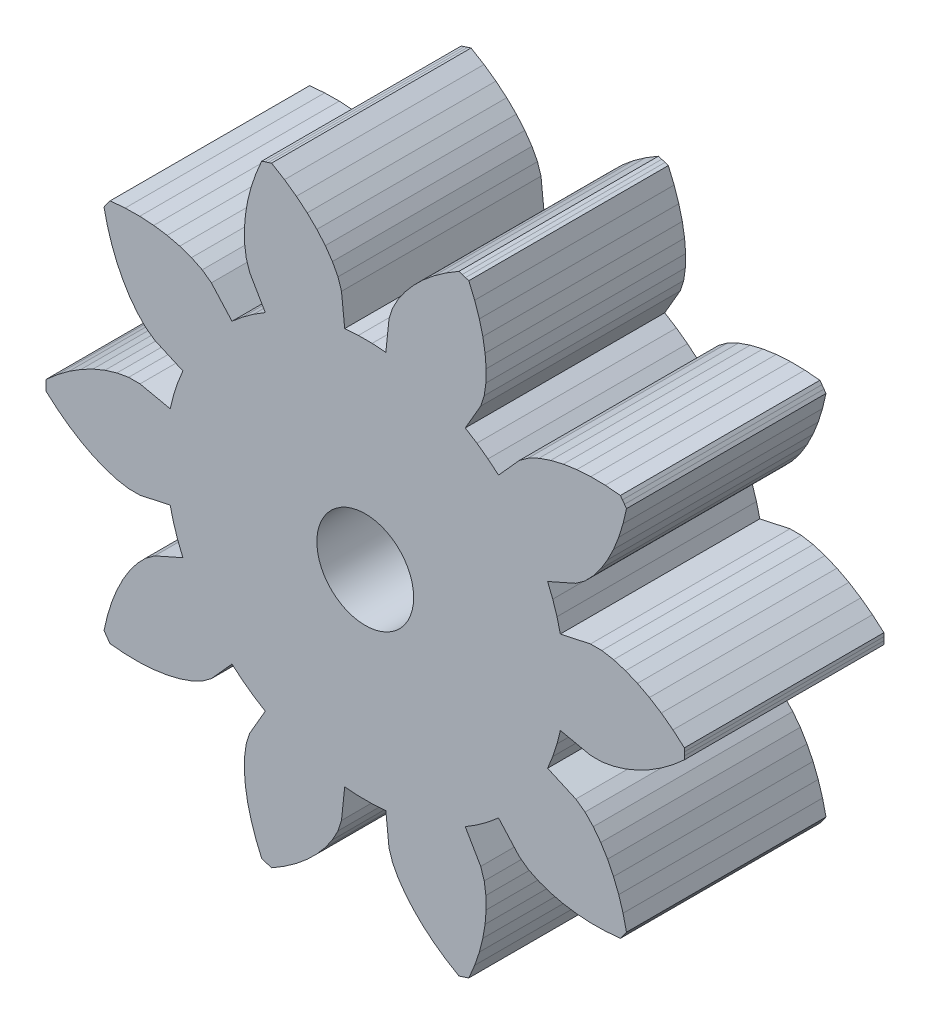
SolidWorks part; units mm, degrees
ref_plane "前视基准面" through (0, 0, 0) normal (0, 0, 1) x (1, 0, 0)
ref_plane "上视基准面" through (0, 0, 0) normal (0, 1, 0) x (1, 0, 0)
ref_plane "右视基准面" through (0, 0, 0) normal (1, 0, 0) x (0, 0, -1)
other "Configuration Table"
sketch "草图1" plane through (0, 0, 0) normal (0, 0, 1) x (1, 0, 0)
  line L0 (14.6679, -3.1391) -> (16.937, -3.6247)
  line L1 (16.937, -3.6247) -> (17.7897, -3.6258)
  line L2 (17.7897, -3.6258) -> (18.6707, -3.47)
  line L3 (18.6707, -3.47) -> (19.5656, -3.1987)
  line L4 (19.5656, -3.1987) -> (20.4663, -2.8243)
  line L5 (20.4663, -2.8243) -> (21.366, -2.3529)
  line L6 (21.366, -2.3529) -> (22.2584, -1.7882)
  line L7 (22.2584, -1.7882) -> (23.1373, -1.133)
  line L8 (23.1373, -1.133) -> (23.9968, -0.3893)
  line L9 (23.9968, -0.3893) -> (23.9996, -0.1298)
  line L10 (23.9996, -0.1298) -> (23.9996, 0.1298)
  line L11 (23.9996, 0.1298) -> (23.9968, 0.3893)
  line L12 (23.9968, 0.3893) -> (23.1373, 1.133)
  line L13 (23.1373, 1.133) -> (22.2584, 1.7882)
  line L14 (22.2584, 1.7882) -> (21.366, 2.3529)
  line L15 (21.366, 2.3529) -> (20.4663, 2.8243)
  line L16 (20.4663, 2.8243) -> (19.5656, 3.1987)
  line L17 (19.5656, 3.1987) -> (18.6707, 3.47)
  line L18 (18.6707, 3.47) -> (17.7897, 3.6258)
  line L19 (17.7897, 3.6258) -> (16.937, 3.6247)
  line L20 (16.937, 3.6247) -> (14.6679, 3.1391)
  line L21 (14.6679, 3.1391) -> (14.417, 4.1412)
  line L22 (14.417, 4.1412) -> (14.0978, 5.1238)
  line L23 (14.0978, 5.1238) -> (13.7117, 6.082)
  line L24 (13.7117, 6.082) -> (15.8329, 7.0229)
  line L25 (15.8329, 7.0229) -> (16.5234, 7.5232)
  line L26 (16.5234, 7.5232) -> (17.1445, 8.167)
  line L27 (17.1445, 8.167) -> (17.709, 8.9125)
  line L28 (17.709, 8.9125) -> (18.2177, 9.7449)
  line L29 (18.2177, 9.7449) -> (18.6685, 10.6551)
  line L30 (18.6685, 10.6551) -> (19.0585, 11.6364)
  line L31 (19.0585, 11.6364) -> (19.3845, 12.6832)
  line L32 (19.3845, 12.6832) -> (19.6427, 13.79)
  line L33 (19.6427, 13.79) -> (19.4924, 14.0016)
  line L34 (19.4924, 14.0016) -> (19.3398, 14.2116)
  line L35 (19.3398, 14.2116) -> (19.185, 14.42)
  line L36 (19.185, 14.42) -> (18.0525, 14.5164)
  line L37 (18.0525, 14.5164) -> (16.9563, 14.5299)
  line L38 (16.9563, 14.5299) -> (15.9025, 14.4622)
  line L39 (15.9025, 14.4622) -> (14.8975, 14.3147)
  line L40 (14.8975, 14.3147) -> (13.9487, 14.0882)
  line L41 (13.9487, 14.0882) -> (13.0653, 13.7816)
  line L42 (13.0653, 13.7816) -> (12.261, 13.3899)
  line L43 (12.261, 13.3899) -> (11.5718, 12.8878)
  line L44 (11.5718, 12.8878) -> (10.0214, 11.1611)
  line L45 (10.0214, 11.1611) -> (9.2294, 11.8244)
  line L46 (9.2294, 11.8244) -> (8.3937, 12.4317)
  line L47 (8.3937, 12.4317) -> (7.5181, 12.9799)
  line L48 (7.5181, 12.9799) -> (8.6811, 14.9879)
  line L49 (8.6811, 14.9879) -> (8.9457, 15.7986)
  line L50 (8.9457, 15.7986) -> (9.0697, 16.6846)
  line L51 (9.0697, 16.6846) -> (9.0883, 17.6195)
  line L52 (9.0883, 17.6195) -> (9.0105, 18.5918)
  line L53 (9.0105, 18.5918) -> (8.8402, 19.5932)
  line L54 (8.8402, 19.5932) -> (8.579, 20.6164)
  line L55 (8.579, 20.6164) -> (8.2274, 21.6548)
  line L56 (8.2274, 21.6548) -> (7.7857, 22.702)
  line L57 (7.7857, 22.702) -> (7.5397, 22.7849)
  line L58 (7.5397, 22.7849) -> (7.2929, 22.8651)
  line L59 (7.2929, 22.8651) -> (7.0451, 22.9427)
  line L60 (7.0451, 22.9427) -> (6.0723, 22.355)
  line L61 (6.0723, 22.355) -> (5.1775, 21.7216)
  line L62 (5.1775, 21.7216) -> (4.3647, 21.0474)
  line L63 (4.3647, 21.0474) -> (3.6383, 20.3374)
  line L64 (3.6383, 20.3374) -> (3.0039, 19.5964)
  line L65 (3.0039, 19.5964) -> (2.4694, 18.8291)
  line L66 (2.4694, 18.8291) -> (2.049, 18.0395)
  line L67 (2.049, 18.0395) -> (1.7865, 17.2281)
  line L68 (1.7865, 17.2281) -> (1.5472, 14.92)
  line L69 (1.5472, 14.92) -> (0.5165, 14.9911)
  line L70 (0.5165, 14.9911) -> (-0.5165, 14.9911)
  line L71 (-0.5165, 14.9911) -> (-1.5472, 14.92)
  line L72 (-1.5472, 14.92) -> (-1.7865, 17.2281)
  line L73 (-1.7865, 17.2281) -> (-2.049, 18.0395)
  line L74 (-2.049, 18.0395) -> (-2.4694, 18.8291)
  line L75 (-2.4694, 18.8291) -> (-3.0039, 19.5964)
  line L76 (-3.0039, 19.5964) -> (-3.6383, 20.3374)
  line L77 (-3.6383, 20.3374) -> (-4.3647, 21.0474)
  line L78 (-4.3647, 21.0474) -> (-5.1775, 21.7216)
  line L79 (-5.1775, 21.7216) -> (-6.0723, 22.355)
  line L80 (-6.0723, 22.355) -> (-7.0451, 22.9427)
  line L81 (-7.0451, 22.9427) -> (-7.2929, 22.8651)
  line L82 (-7.2929, 22.8651) -> (-7.5397, 22.7849)
  line L83 (-7.5397, 22.7849) -> (-7.7857, 22.702)
  line L84 (-7.7857, 22.702) -> (-8.2274, 21.6548)
  line L85 (-8.2274, 21.6548) -> (-8.579, 20.6164)
  line L86 (-8.579, 20.6164) -> (-8.8402, 19.5932)
  line L87 (-8.8402, 19.5932) -> (-9.0105, 18.5918)
  line L88 (-9.0105, 18.5918) -> (-9.0883, 17.6195)
  line L89 (-9.0883, 17.6195) -> (-9.0697, 16.6846)
  line L90 (-9.0697, 16.6846) -> (-8.9457, 15.7986)
  line L91 (-8.9457, 15.7986) -> (-8.6811, 14.9879)
  line L92 (-8.6811, 14.9879) -> (-7.5181, 12.9799)
  line L93 (-7.5181, 12.9799) -> (-8.3937, 12.4317)
  line L94 (-8.3937, 12.4317) -> (-9.2294, 11.8244)
  line L95 (-9.2294, 11.8244) -> (-10.0214, 11.1611)
  line L96 (-10.0214, 11.1611) -> (-11.5718, 12.8878)
  line L97 (-11.5718, 12.8878) -> (-12.261, 13.3899)
  line L98 (-12.261, 13.3899) -> (-13.0653, 13.7816)
  line L99 (-13.0653, 13.7816) -> (-13.9487, 14.0882)
  line L100 (-13.9487, 14.0882) -> (-14.8975, 14.3147)
  line L101 (-14.8975, 14.3147) -> (-15.9025, 14.4622)
  line L102 (-15.9025, 14.4622) -> (-16.9563, 14.5299)
  line L103 (-16.9563, 14.5299) -> (-18.0525, 14.5164)
  line L104 (-18.0525, 14.5164) -> (-19.185, 14.42)
  line L105 (-19.185, 14.42) -> (-19.3398, 14.2116)
  line L106 (-19.3398, 14.2116) -> (-19.4924, 14.0016)
  line L107 (-19.4924, 14.0016) -> (-19.6427, 13.79)
  line L108 (-19.6427, 13.79) -> (-19.3845, 12.6832)
  line L109 (-19.3845, 12.6832) -> (-19.0585, 11.6364)
  line L110 (-19.0585, 11.6364) -> (-18.6685, 10.6551)
  line L111 (-18.6685, 10.6551) -> (-18.2177, 9.7449)
  line L112 (-18.2177, 9.7449) -> (-17.709, 8.9125)
  line L113 (-17.709, 8.9125) -> (-17.1445, 8.167)
  line L114 (-17.1445, 8.167) -> (-16.5234, 7.5232)
  line L115 (-16.5234, 7.5232) -> (-15.8329, 7.0229)
  line L116 (-15.8329, 7.0229) -> (-13.7117, 6.082)
  line L117 (-13.7117, 6.082) -> (-14.0978, 5.1238)
  line L118 (-14.0978, 5.1238) -> (-14.417, 4.1412)
  line L119 (-14.417, 4.1412) -> (-14.6679, 3.1391)
  line L120 (-14.6679, 3.1391) -> (-16.937, 3.6247)
  line L121 (-16.937, 3.6247) -> (-17.7897, 3.6258)
  line L122 (-17.7897, 3.6258) -> (-18.6707, 3.47)
  line L123 (-18.6707, 3.47) -> (-19.5656, 3.1987)
  line L124 (-19.5656, 3.1987) -> (-20.4663, 2.8243)
  line L125 (-20.4663, 2.8243) -> (-21.366, 2.3529)
  line L126 (-21.366, 2.3529) -> (-22.2584, 1.7882)
  line L127 (-22.2584, 1.7882) -> (-23.1373, 1.133)
  line L128 (-23.1373, 1.133) -> (-23.9968, 0.3893)
  line L129 (-23.9968, 0.3893) -> (-23.9996, 0.1298)
  line L130 (-23.9996, 0.1298) -> (-23.9996, -0.1298)
  line L131 (-23.9996, -0.1298) -> (-23.9968, -0.3893)
  line L132 (-23.9968, -0.3893) -> (-23.1373, -1.133)
  line L133 (-23.1373, -1.133) -> (-22.2584, -1.7882)
  line L134 (-22.2584, -1.7882) -> (-21.366, -2.3529)
  line L135 (-21.366, -2.3529) -> (-20.4663, -2.8243)
  line L136 (-20.4663, -2.8243) -> (-19.5656, -3.1987)
  line L137 (-19.5656, -3.1987) -> (-18.6707, -3.47)
  line L138 (-18.6707, -3.47) -> (-17.7897, -3.6258)
  line L139 (-17.7897, -3.6258) -> (-16.937, -3.6247)
  line L140 (-16.937, -3.6247) -> (-14.6679, -3.1391)
  line L141 (-14.6679, -3.1391) -> (-14.417, -4.1412)
  line L142 (-14.417, -4.1412) -> (-14.0978, -5.1238)
  line L143 (-14.0978, -5.1238) -> (-13.7117, -6.082)
  line L144 (-13.7117, -6.082) -> (-15.8329, -7.0229)
  line L145 (-15.8329, -7.0229) -> (-16.5234, -7.5232)
  line L146 (-16.5234, -7.5232) -> (-17.1445, -8.167)
  line L147 (-17.1445, -8.167) -> (-17.709, -8.9125)
  line L148 (-17.709, -8.9125) -> (-18.2177, -9.7449)
  line L149 (-18.2177, -9.7449) -> (-18.6685, -10.6551)
  line L150 (-18.6685, -10.6551) -> (-19.0585, -11.6364)
  line L151 (-19.0585, -11.6364) -> (-19.3845, -12.6832)
  line L152 (-19.3845, -12.6832) -> (-19.6427, -13.79)
  line L153 (-19.6427, -13.79) -> (-19.4924, -14.0016)
  line L154 (-19.4924, -14.0016) -> (-19.3398, -14.2116)
  line L155 (-19.3398, -14.2116) -> (-19.185, -14.42)
  line L156 (-19.185, -14.42) -> (-18.0525, -14.5164)
  line L157 (-18.0525, -14.5164) -> (-16.9563, -14.5299)
  line L158 (-16.9563, -14.5299) -> (-15.9025, -14.4622)
  line L159 (-15.9025, -14.4622) -> (-14.8975, -14.3147)
  line L160 (-14.8975, -14.3147) -> (-13.9487, -14.0882)
  line L161 (-13.9487, -14.0882) -> (-13.0653, -13.7816)
  line L162 (-13.0653, -13.7816) -> (-12.261, -13.3899)
  line L163 (-12.261, -13.3899) -> (-11.5718, -12.8878)
  line L164 (-11.5718, -12.8878) -> (-10.0214, -11.1611)
  line L165 (-10.0214, -11.1611) -> (-9.2294, -11.8244)
  line L166 (-9.2294, -11.8244) -> (-8.3937, -12.4317)
  line L167 (-8.3937, -12.4317) -> (-7.5181, -12.9799)
  line L168 (-7.5181, -12.9799) -> (-8.6811, -14.9879)
  line L169 (-8.6811, -14.9879) -> (-8.9457, -15.7986)
  line L170 (-8.9457, -15.7986) -> (-9.0697, -16.6846)
  line L171 (-9.0697, -16.6846) -> (-9.0883, -17.6195)
  line L172 (-9.0883, -17.6195) -> (-9.0105, -18.5918)
  line L173 (-9.0105, -18.5918) -> (-8.8402, -19.5932)
  line L174 (-8.8402, -19.5932) -> (-8.579, -20.6164)
  line L175 (-8.579, -20.6164) -> (-8.2274, -21.6548)
  line L176 (-8.2274, -21.6548) -> (-7.7857, -22.702)
  line L177 (-7.7857, -22.702) -> (-7.5397, -22.7849)
  line L178 (-7.5397, -22.7849) -> (-7.2929, -22.8651)
  line L179 (-7.2929, -22.8651) -> (-7.0451, -22.9427)
  line L180 (-7.0451, -22.9427) -> (-6.0723, -22.355)
  line L181 (-6.0723, -22.355) -> (-5.1775, -21.7216)
  line L182 (-5.1775, -21.7216) -> (-4.3647, -21.0474)
  line L183 (-4.3647, -21.0474) -> (-3.6383, -20.3374)
  line L184 (-3.6383, -20.3374) -> (-3.0039, -19.5964)
  line L185 (-3.0039, -19.5964) -> (-2.4694, -18.8291)
  line L186 (-2.4694, -18.8291) -> (-2.049, -18.0395)
  line L187 (-2.049, -18.0395) -> (-1.7865, -17.2281)
  line L188 (-1.7865, -17.2281) -> (-1.5472, -14.92)
  line L189 (-1.5472, -14.92) -> (-0.5165, -14.9911)
  line L190 (-0.5165, -14.9911) -> (0.5165, -14.9911)
  line L191 (0.5165, -14.9911) -> (1.5472, -14.92)
  line L192 (1.5472, -14.92) -> (1.7865, -17.2281)
  line L193 (1.7865, -17.2281) -> (2.049, -18.0395)
  line L194 (2.049, -18.0395) -> (2.4694, -18.8291)
  line L195 (2.4694, -18.8291) -> (3.0039, -19.5964)
  line L196 (3.0039, -19.5964) -> (3.6383, -20.3374)
  line L197 (3.6383, -20.3374) -> (4.3647, -21.0474)
  line L198 (4.3647, -21.0474) -> (5.1775, -21.7216)
  line L199 (5.1775, -21.7216) -> (6.0723, -22.355)
  line L200 (6.0723, -22.355) -> (7.0451, -22.9427)
  line L201 (7.0451, -22.9427) -> (7.2929, -22.8651)
  line L202 (7.2929, -22.8651) -> (7.5397, -22.7849)
  line L203 (7.5397, -22.7849) -> (7.7857, -22.702)
  line L204 (7.7857, -22.702) -> (8.2274, -21.6548)
  line L205 (8.2274, -21.6548) -> (8.579, -20.6164)
  line L206 (8.579, -20.6164) -> (8.8402, -19.5932)
  line L207 (8.8402, -19.5932) -> (9.0105, -18.5918)
  line L208 (9.0105, -18.5918) -> (9.0883, -17.6195)
  line L209 (9.0883, -17.6195) -> (9.0697, -16.6846)
  line L210 (9.0697, -16.6846) -> (8.9457, -15.7986)
  line L211 (8.9457, -15.7986) -> (8.6811, -14.9879)
  line L212 (8.6811, -14.9879) -> (7.5181, -12.9799)
  line L213 (7.5181, -12.9799) -> (8.3937, -12.4317)
  line L214 (8.3937, -12.4317) -> (9.2294, -11.8244)
  line L215 (9.2294, -11.8244) -> (10.0214, -11.1611)
  line L216 (10.0214, -11.1611) -> (11.5718, -12.8878)
  line L217 (11.5718, -12.8878) -> (12.261, -13.3899)
  line L218 (12.261, -13.3899) -> (13.0653, -13.7816)
  line L219 (13.0653, -13.7816) -> (13.9487, -14.0882)
  line L220 (13.9487, -14.0882) -> (14.8975, -14.3147)
  line L221 (14.8975, -14.3147) -> (15.9025, -14.4622)
  line L222 (15.9025, -14.4622) -> (16.9563, -14.5299)
  line L223 (16.9563, -14.5299) -> (18.0525, -14.5164)
  line L224 (18.0525, -14.5164) -> (19.185, -14.42)
  line L225 (19.185, -14.42) -> (19.3398, -14.2116)
  line L226 (19.3398, -14.2116) -> (19.4924, -14.0016)
  line L227 (19.4924, -14.0016) -> (19.6427, -13.79)
  line L228 (19.6427, -13.79) -> (19.3845, -12.6832)
  line L229 (19.3845, -12.6832) -> (19.0585, -11.6364)
  line L230 (19.0585, -11.6364) -> (18.6685, -10.6551)
  line L231 (18.6685, -10.6551) -> (18.2177, -9.7449)
  line L232 (18.2177, -9.7449) -> (17.709, -8.9125)
  line L233 (17.709, -8.9125) -> (17.1445, -8.167)
  line L234 (17.1445, -8.167) -> (16.5234, -7.5232)
  line L235 (16.5234, -7.5232) -> (15.8329, -7.0229)
  line L236 (15.8329, -7.0229) -> (13.7117, -6.082)
  line L237 (13.7117, -6.082) -> (14.0978, -5.1238)
  line L238 (14.0978, -5.1238) -> (14.417, -4.1412)
  line L239 (14.417, -4.1412) -> (14.6679, -3.1391)
  circle A0 centre (0, 0) radius 3.6383
extrude "凸台-拉伸1" add sketch "草图1" along normal blind 15
